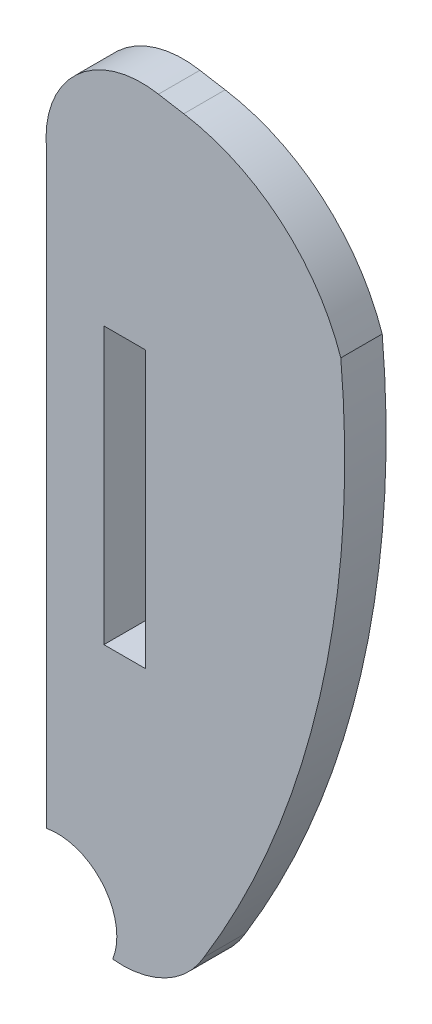
SolidWorks part; units mm, degrees
ref_plane "Front" through (0, 0, 0) normal (0, 0, 1) x (1, 0, 0)
ref_plane "Top" through (0, 0, 0) normal (0, 1, 0) x (1, 0, 0)
ref_plane "Right" through (0, 0, 0) normal (1, 0, 0) x (0, 0, -1)
sketch "Sketch1" plane through (0, 0, 0) normal (0, 0, 1) x (1, 0, 0)
  line L0 (498.0032, 62.3139) -> (495.0032, 62.3139)
  line L1 (495.0032, 62.3139) -> (495.0032, 82.3139)
  line L2 (495.0032, 82.3139) -> (498.0032, 82.3139)
  line L3 (498.0032, 82.3139) -> (498.0032, 62.3139)
  line L4 (490.8593, 48.7114) -> (490.8593, 91.1786)
  arc A0 (502.2484, 46.3138) -> (512.1671, 88.8889) centre (442.7571, 82.6164) ccw
  arc A1 (490.8593, 48.7114) -> (495.646, 42.8989) centre (491.6257, 44.4654) cw
  arc A2 (500.7895, 98.5198) -> (498.9588, 98.8319) centre (520.0387, 216.9659) cw
  arc A4 (502.2484, 46.3138) -> (495.646, 42.8989) centre (496.3346, 49.6576) cw
  arc A6 (490.8593, 91.1786) -> (498.9588, 98.8319) centre (497.7412, 92.008) cw
  arc A7 (500.7895, 98.5198) -> (512.1671, 88.8889) centre (498.4693, 84.2428) cw
  dimension "D2" = 20
  dimension "D1" = 3
extrude "Base-Extrude" add sketch "Sketch1" along normal blind 3
